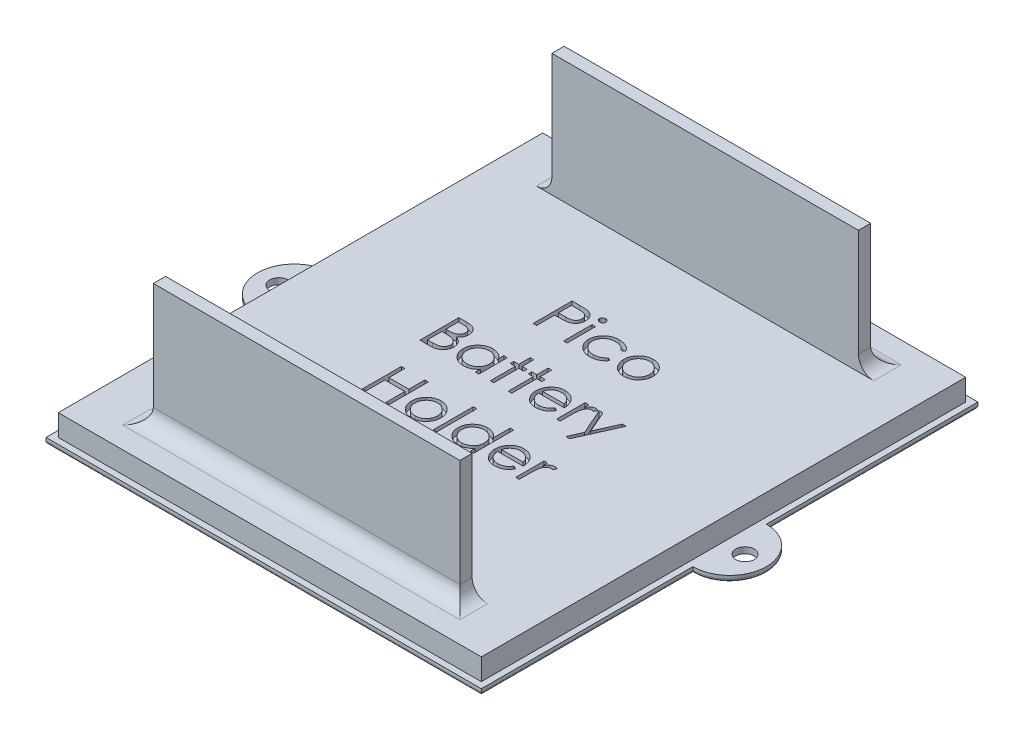
SolidWorks part; units mm, degrees
other "Markup1"
sketch "Sketch11" plane through (-41.5, 7, -35.5) normal (0, 1, 0) x (1, 0, 0)
sketch "Sketch12" plane through (-41.5, 7, -35.5) normal (0, 1, 0) x (1, 0, 0)
sketch "Sketch13" plane through (-41.5, 7, -35.5) normal (0, 1, 0) x (1, 0, 0)
sketch "Sketch15" plane through (-41.5, 7, -35.5) normal (0, 1, 0) x (1, 0, 0)
sketch "Sketch16" plane through (-41.5, 7, -35.5) normal (0, 1, 0) x (1, 0, 0)
sketch "Sketch17" plane through (-41.5, 7, -35.5) normal (0, 1, 0) x (1, 0, 0)
sketch "Sketch18" plane through (-41.5, 7, -35.5) normal (0, 1, 0) x (1, 0, 0)
sketch "Sketch19" plane through (-41.5, 7, -35.5) normal (0, 1, 0) x (1, 0, 0)
sketch "Sketch20" plane through (-41.5, 12, -35.5) normal (0, 1, 0) x (1, 0, 0)
sketch "Sketch21" plane through (-41.5, 12, -35.5) normal (0, 1, 0) x (1, 0, 0)
sketch "Sketch22" plane through (-41.5, 12, -35.5) normal (0, 1, 0) x (1, 0, 0)
sketch "Sketch31" plane through (-41.5, 25.5, -40.5) normal (0, 1, 0) x (1, 0, 0)
sketch "Sketch32" plane through (-41.5, 25.5, -40.5) normal (0, 1, 0) x (1, 0, 0)
sketch "Sketch38" plane through (-41.5, 25.5, -40.5) normal (0, 1, 0) x (1, 0, 0)
sketch "Sketch39" plane through (-41.5, 25.5, -40.5) normal (0, 1, 0) x (1, 0, 0)
sketch "Sketch40" plane through (-41.5, 25.5, -40.5) normal (0, 1, 0) x (1, 0, 0)
sketch "Sketch41" plane through (-41.5, 24.5, -40.5) normal (0, 1, 0) x (1, 0, 0)
sketch "Sketch48" plane through (-41.5, 24.5, -40.5) normal (0, 1, 0) x (1, 0, 0)
sketch "Sketch49" plane through (-41.5, 24.5, -40.5) normal (0, 1, 0) x (1, 0, 0)
sketch "Sketch50" plane through (-41.5, 24.5, -40.5) normal (0, 1, 0) x (1, 0, 0)
ref_plane "Front Plane" through (0, 0, 0) normal (0, 0, 1) x (1, 0, 0)
ref_plane "Top Plane" through (0, 0, 0) normal (0, 1, 0) x (1, 0, 0)
ref_plane "Right Plane" through (0, 0, 0) normal (1, 0, 0) x (0, 0, -1)
sketch "Sketch1" plane through (0, 0, 0) normal (0, 1, 0) x (1, 0, 0)
  line L1 (-35.5, -40.5) -> (35.5, -40.5)
  line L2 (-35.5, -40.5) -> (-35.5, 40.5)
  line L3 (-35.5, 40.5) -> (35.5, 40.5)
  line L4 (35.5, -40.5) -> (35.5, 40.5)
  line L5 (-35.5, -40.5) -> (35.5, 40.5) construction
  line L6 (-35.5, 40.5) -> (35.5, -40.5) construction
  point P0 (0, 0)
  point P6 (0, 0)
  dimension "D1" = 81
  dimension "D2" = 71
extrude "Boss-Extrude1" add sketch "Sketch1" along normal blind 4.5
sketch "text" plane through (0, 4.5, 0) normal (0, 1, 0) x (1, 0, 0)
  line L0 (-35.4043, 11.8177) -> (35.5957, 11.8177) construction
  text T0 "Pico\r\nBattery \r\nHolder" font "Century Gothic" height in points 24
extrude "Cut-Extrude1" cut sketch "text" against normal blind 1
sketch "Sketch4" plane through (0, 4.5, 0) normal (0, 1, 0) x (1, 0, 0)
  line L0 (-35.5, 40.5) -> (-35.5, -40.5) construction
  line L1 (-35.5, 6) -> (-35.5, -6)
  arc A0 (-35.5, 6) -> (-35.5, -6) centre (-35.5, 0) ccw
  dimension "D1" = 6
extrude "Boss-Extrude3" add sketch "Sketch4" against normal up to surface (4.5 mm away) up to face at (0, 0, 0)
sketch "Sketch5" plane through (0, 4.5, 0) normal (0, 1, 0) x (1, 0, 0)
  line L0 (-35.5, 40.5) -> (-35.5, 6) construction
  circle A0 centre (-38, 0) radius 1.5
  dimension "D1" = 3
  dimension "D2" = 2.5
extrude "Cut-Extrude2" cut sketch "Sketch5" against normal up to surface (4.5 mm away) up to face at (-12.8333, 0, 0)
mirror "Mirror3" about plane through (0, 0, 0) normal (1, 0, 0) of "Boss-Extrude3", "Cut-Extrude2"
sketch "Sketch9" plane through (0, 4.5, 0) normal (0, 1, 0) x (1, 0, 0)
  line L0 (35.5, 40.5) -> (-35.5, 40.5) construction
  line L1 (-25, 33.5) -> (25, 33.5)
  line L2 (-25, 33.5) -> (-25, 31.5)
  line L3 (-25, 31.5) -> (25, 31.5)
  line L4 (25, 33.5) -> (25, 31.5)
  line L5 (-55, 0) -> (55, 0) construction
  point P5 (0, 33.5)
  point P8 (0, 40.5)
  dimension "D1" = 50
  dimension "D2" = 2
  dimension "D3" = 31.5
extrude "top track" add sketch "Sketch9" along normal blind 20 contours L2 L1 L4 L3
sketch "Sketch51" plane through (0, 4.5, 0) normal (0, 1, 0) x (1, 0, 0)
  line L0 (-35.5, 40.5) -> (-35.5, 6) construction
  line L1 (34.5, 39.5) -> (-34.5, 39.5)
  line L2 (34.5, 39.5) -> (34.5, -39.5)
  line L3 (34.5, -39.5) -> (-34.5, -39.5)
  line L4 (-34.5, 39.5) -> (-34.5, -39.5)
  line L5 (34.5, 39.5) -> (-34.5, -39.5) construction
  line L6 (34.5, -39.5) -> (-34.5, 39.5) construction
  line L7 (35.5, 40.5) -> (-35.5, 40.5) construction
  line L8 (-44.5, 49.5) -> (-44.5, -49.5)
  line L9 (44.5, -49.5) -> (-44.5, -49.5)
  line L10 (44.5, 49.5) -> (44.5, -49.5)
  line L11 (44.5, 49.5) -> (-44.5, 49.5)
  point P0 (0, 0)
  dimension "D1" = 1
  dimension "D2" = 1
  dimension "D3" = 10
extrude "Cut-Extrude25" cut sketch "Sketch51" against normal blind 3.5
fillet "Fillet2" radius 0.5 8 edges at (-35.5, 0, -23.25) (-41.5, 0, 0) (-35.5, 0, 23.25) (0, 0, 40.5) (35.5, 0, 23.25) (41.5, 0, 0) (35.5, 0, -23.25) (0, 0, -40.5)
fillet "Fillet3" radius 2.5 3 edges at (25, 4.5, -32.5) (0, 4.5, -33.5) (-25, 4.5, -32.5)
mirror "Mirror4" about plane through (0, 0, 0) normal (0, 0, 1) of "Fillet3", "top track"
equation "\"Screw_Diameter\"=3"
